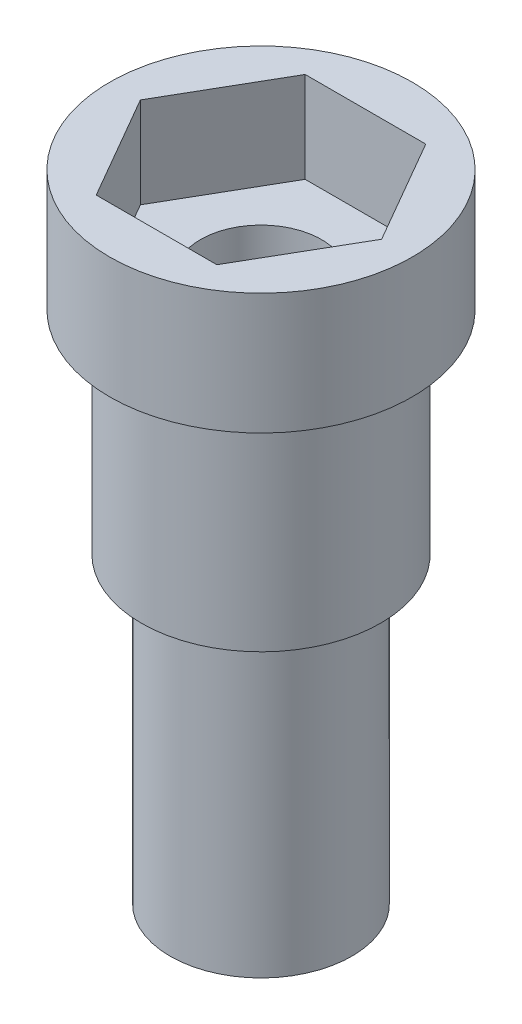
SolidWorks part; units mm, degrees
ref_plane "Front Plane" through (0, 0, 0) normal (0, 0, 1) x (1, 0, 0)
ref_plane "Top Plane" through (0, 0, 0) normal (0, 1, 0) x (1, 0, 0)
ref_plane "Right Plane" through (0, 0, 0) normal (1, 0, 0) x (0, 0, -1)
sketch "Sketch1" plane through (0, 0, 0) normal (0, 1, 0) x (1, 0, 0)
  circle A0 centre (0, 0) radius 3
  circle A1 centre (0, 0) radius 2
  dimension "D1" = 6
  dimension "D2" = 4
extrude "Boss-Extrude1" add sketch "Sketch1" along normal blind 18
sketch "Sketch2" plane through (0, 18, 0) normal (0, 1, 0) x (1, 0, 0)
  circle A0 centre (0, 0) radius 2
  circle A1 centre (0, 0) radius 3.95
  dimension "D1" = 4
  dimension "D2" = 7.9
extrude "Boss-Extrude3" add sketch "Sketch2" along normal blind 7 from offset 8 offset against normal yes
sketch "Sketch4" plane through (0, 17, 0) normal (0, 1, 0) x (1, 0, 0)
  circle A0 centre (0, 0) radius 2 construction
  circle A1 centre (0, 0) radius 2
  circle A2 centre (0, 0) radius 5
  dimension "D1" = 10
extrude "Boss-Extrude4" add sketch "Sketch4" along normal blind 4
sketch "Sketch5" plane through (0, 21, 0) normal (0, 1, 0) x (1, 0, 0)
  line L1 (3.9837, 0) -> (1.9919, 3.45)
  line L2 (1.9919, 3.45) -> (-1.9919, 3.45)
  line L3 (-1.9919, 3.45) -> (-3.9837, 0)
  line L4 (-3.9837, 0) -> (-1.9919, -3.45)
  line L5 (-1.9919, -3.45) -> (1.9919, -3.45)
  line L6 (1.9919, -3.45) -> (3.9837, 0)
  circle A0 centre (0, 0) radius 3.45 construction
  dimension "D1" = 6.9
extrude "Cut-Extrude1" cut sketch "Sketch5" against normal blind 3 contours L1 L2 L3 L4 L5 L6
